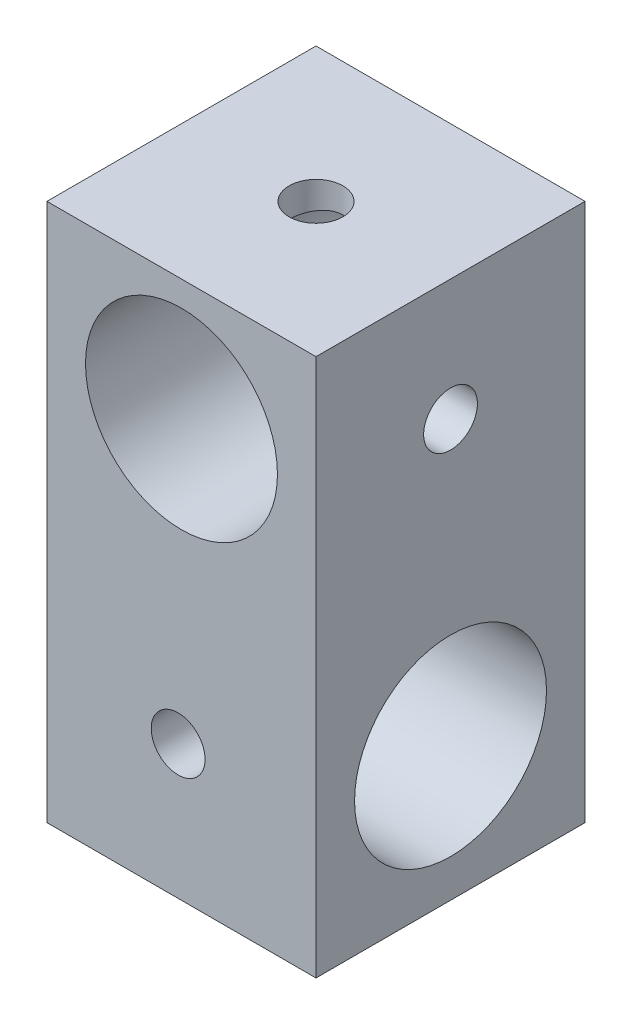
SolidWorks part; units mm, degrees
ref_plane "前视基准面" through (0, 0, 0) normal (0, 0, 1) x (1, 0, 0)
ref_plane "上视基准面" through (0, 0, 0) normal (0, 1, 0) x (1, 0, 0)
ref_plane "右视基准面" through (0, 0, 0) normal (1, 0, 0) x (0, 0, -1)
sketch "草图1" plane through (0, 0, 0) normal (1, 0, 0) x (0, 0, -1)
  line L1 (7.5, -15) -> (-7.5, -15)
  line L2 (7.5, -15) -> (7.5, 15)
  line L3 (7.5, 15) -> (-7.5, 15)
  line L4 (-7.5, -15) -> (-7.5, 15)
  line L5 (7.5, -15) -> (-7.5, 15) construction
  line L6 (7.5, 15) -> (-7.5, -15) construction
  point P0 (0, 0)
extrude "凸台-拉伸1" add sketch "草图1" along normal blind 15
sketch "草图2" plane through (15, 0, 0) normal (1, 0, 0) x (0, 0, -1)
  circle A0 centre (0, -7.5379) radius 5.35
extrude "切除-拉伸1" cut sketch "草图2" against normal blind 15
sketch "草图4" plane through (0, 0, 7.5) normal (0, 0, 1) x (1, 0, 0)
  line L0 (7.5, 15) -> (7.5, -15) construction
  line L1 (15, 15) -> (0, 15) construction
  line L2 (15, -15) -> (0, -15) construction
  circle A0 centre (7.5, 8.2426) radius 5.35
extrude "切除-拉伸2" cut sketch "草图4" against normal blind 15
sketch "草图5" plane through (0, 0, 7.5) normal (0, 0, 1) x (1, 0, 0)
  line L0 (7.3143, -15) -> (7.3143, -7.54) construction
  line L1 (15, -15) -> (0, -15) construction
  circle A0 centre (7.3143, -7.54) radius 1.5
extrude "切除-拉伸3" cut sketch "草图5" against normal blind 20
sketch "草图7" plane through (15, 0, 0) normal (1, 0, 0) x (0, 0, -1)
  line L0 (0, 15) -> (0, 8.24) construction
  line L1 (7.5, 15) -> (-7.5, 15) construction
  circle A0 centre (0, 8.24) radius 1.5
extrude "切除-拉伸4" cut sketch "草图7" against normal blind 20
sketch "草图8" plane through (0, -15, 0) normal (0, -1, 0) x (1, 0, 0)
  line L0 (7.5, -7.5) -> (7.5, 7.5) construction
  line L1 (15, -7.5) -> (0, -7.5) construction
  line L2 (15, 7.5) -> (0, 7.5) construction
  circle A0 centre (7.5, 0) radius 1.5
extrude "切除-拉伸5" cut sketch "草图8" against normal blind 50
